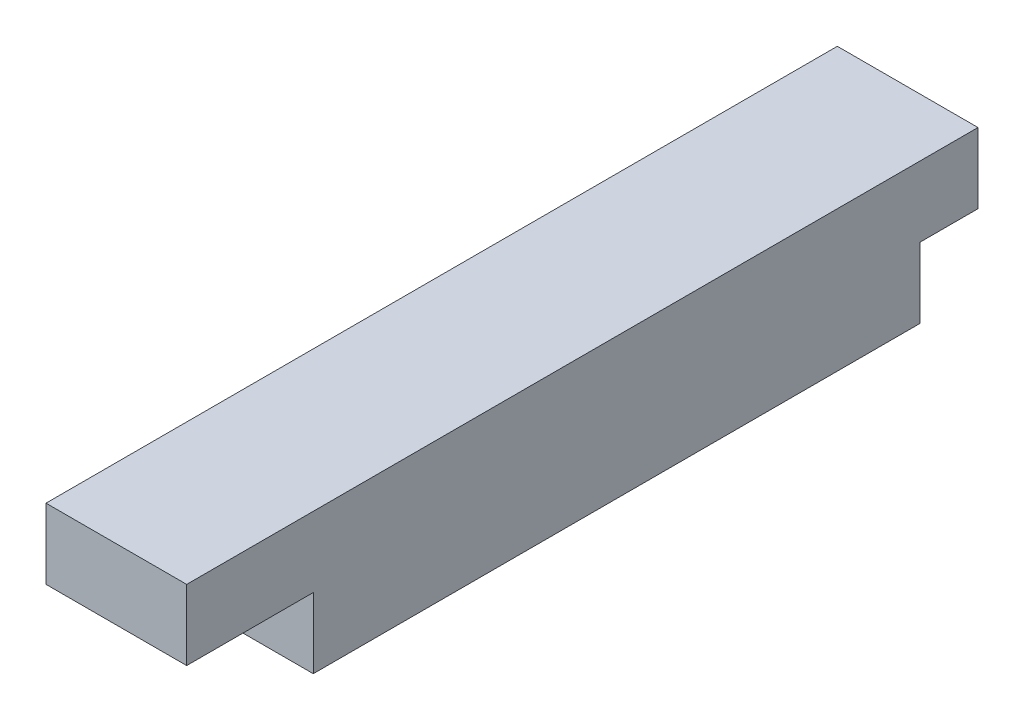
SolidWorks part; units mm, degrees
ref_plane "Alzado" through (0, 0, 0) normal (0, 0, 1) x (1, 0, 0)
ref_plane "Planta" through (0, 0, 0) normal (0, 1, 0) x (1, 0, 0)
ref_plane "Vista lateral" through (0, 0, 0) normal (1, 0, 0) x (0, 0, -1)
sketch "Croquis1" plane through (0, 0, 0) normal (0, 1, 0) x (1, 0, 0)
  line L1 (0, 0) -> (8, 0)
  line L2 (0, 0) -> (0, 45)
  line L3 (0, 45) -> (8, 45)
  line L4 (8, 0) -> (8, 45)
  dimension "D1" = 45
  dimension "D2" = 8
extrude "Saliente-Extruir1" add sketch "Croquis1" along normal blind 4
sketch "Croquis2" plane through (0, 0, 0) normal (0, -1, 0) x (1, 0, 0)
  line L0 (8, 0) -> (8, -45) construction
  line L1 (8, -41.7) -> (3, -41.7)
  line L2 (8, -41.7) -> (8, -7.2)
  line L3 (8, -7.2) -> (3, -7.2)
  line L4 (3, -41.7) -> (3, -7.2)
  line L5 (0, -45) -> (0, 0) construction
  line L6 (0, 0) -> (8, 0) construction
  dimension "D1" = 3
  dimension "D2" = 7.2
  dimension "D3" = 34.5
extrude "Saliente-Extruir2" add sketch "Croquis2" along normal blind 4
